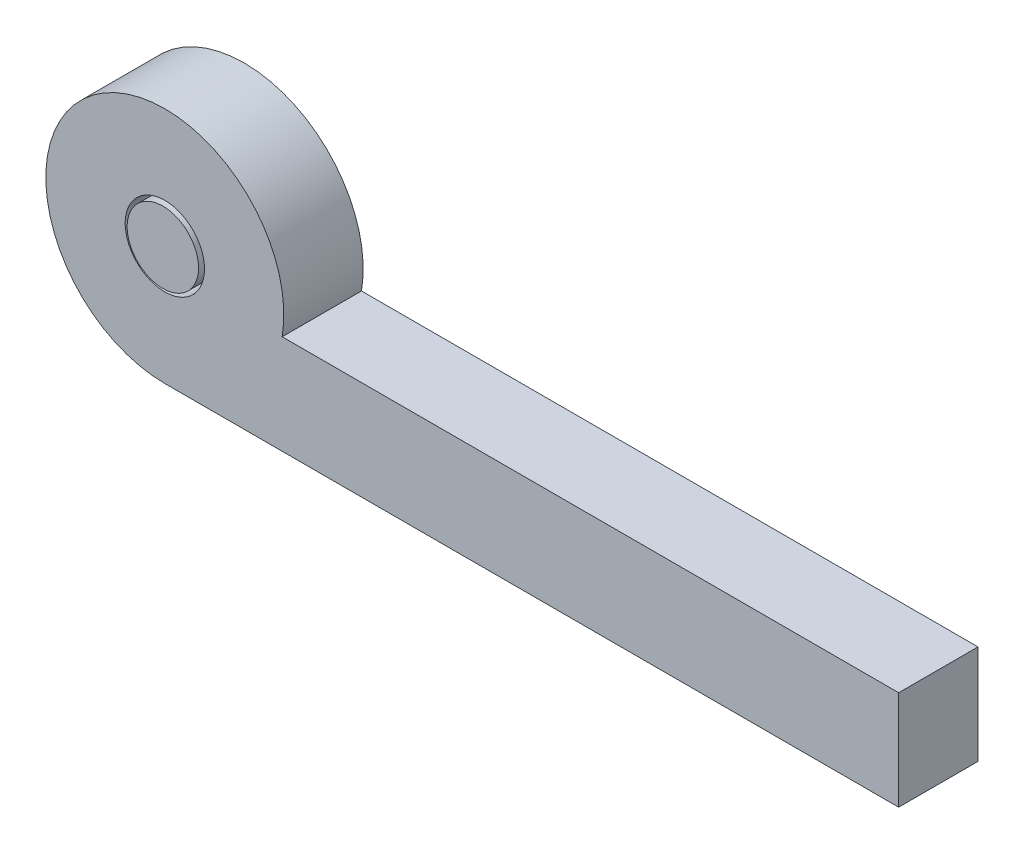
SolidWorks part; units mm, degrees
ref_plane "Front Plane" through (0, 0, 0) normal (0, 0, 1) x (1, 0, 0)
ref_plane "Top Plane" through (0, 0, 0) normal (0, 1, 0) x (1, 0, 0)
ref_plane "Right Plane" through (0, 0, 0) normal (1, 0, 0) x (0, 0, -1)
sketch "Sketch1" plane through (0, 0, 0) normal (0, 0, 1) x (1, 0, 0)
  circle A0 centre (-73.025, -41.275) radius 19.05
  arc A1 (-62.6235, -41.7855) -> (-73.025, -51.689) centre (-73.025, -41.275) ccw construction
  dimension "D1" = 38.1
extrude "Boss-Extrude1" add sketch "Sketch1" along normal mid plane 12.7
sketch "Sketch2" plane through (0, 0, 6.35) normal (0, 0, 1) x (1, 0, 0)
  line L0 (-54.2414, -44.45) -> (44.45, -44.45)
  line L1 (44.45, -44.45) -> (44.45, -60.325)
  line L2 (44.45, -60.325) -> (-73.025, -60.325)
  line L3 (44.45, -44.45) -> (-44.45, -44.45) construction
  line L5 (44.45, 38.1) -> (44.45, -38.1) construction
  circle A0 centre (-73.025, -41.275) radius 19.05 construction
  arc A1 (-73.025, -60.325) -> (-54.2414, -44.45) centre (-73.025, -41.275) ccw
extrude "Boss-Extrude2" add sketch "Sketch2" against normal up to surface (12.7 mm away) up to face at (-53.975, -41.275, -6.35)
sketch "Sketch3" plane through (0, 0, 6.35) normal (0, 0, 1) x (1, 0, 0)
  circle A0 centre (-73.025, -41.275) radius 6.35
  dimension "D1" = 12.7
extrude "Cut-Extrude1" cut sketch "Sketch3" against normal through all
sketch "Sketch4" plane through (0, 0, 0) normal (0, 0, 1) x (1, 0, 0)
  circle A0 centre (-73.025, -41.275) radius 5.715
  dimension "D1" = 11.43
extrude "Boss-Extrude3" add sketch "Sketch4" against normal mid plane 13.335 separate body
